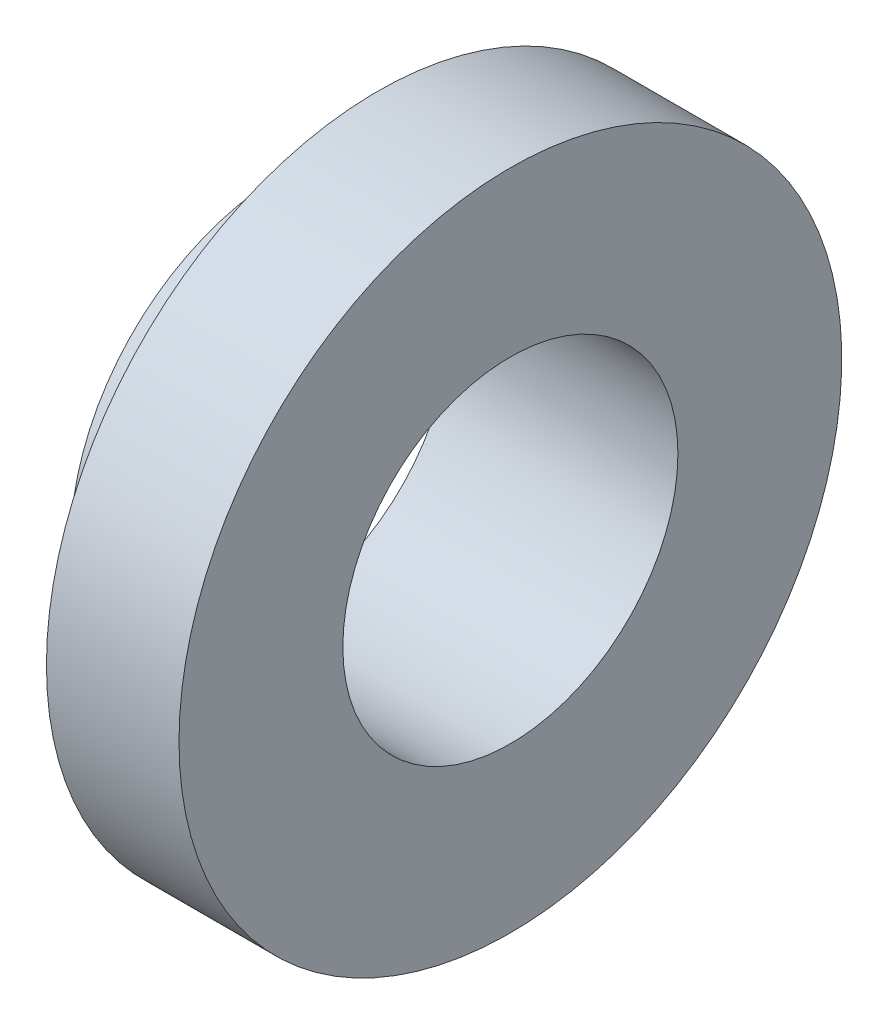
SolidWorks part; units mm, degrees
ref_plane "Front" through (0, 0, 0) normal (0, 0, 1) x (1, 0, 0)
ref_plane "Top" through (0, 0, 0) normal (0, 1, 0) x (1, 0, 0)
ref_plane "Right" through (0, 0, 0) normal (1, 0, 0) x (0, 0, -1)
sketch "Sketch2" plane through (0, 0, 0) normal (0, 0, 1) x (1, 0, 0)
  line L0 (2.2752, 7.9375) -> (2.2752, 5.08)
  line L1 (0, 0) -> (5.4502, 0) construction
  line L2 (0, 4.0132) -> (0, 5.08)
  line L3 (2.2752, 7.9375) -> (5.4502, 7.9375)
  line L4 (5.4502, 4.0132) -> (5.4502, 7.9375)
  line L5 (2.2752, 5.08) -> (0, 5.08)
  line L7 (5.4502, 4.4993) -> (5.4502, 5.417) construction
  line L8 (0, 4.0132) -> (5.4502, 4.0132)
  dimension "D1" = 10.16
  dimension "D2" = 15.875
  dimension "D3" = 3.175
  dimension "D4" = 8.0264
revolve "Revolve1" add sketch "Sketch2" angle 360 about L1
